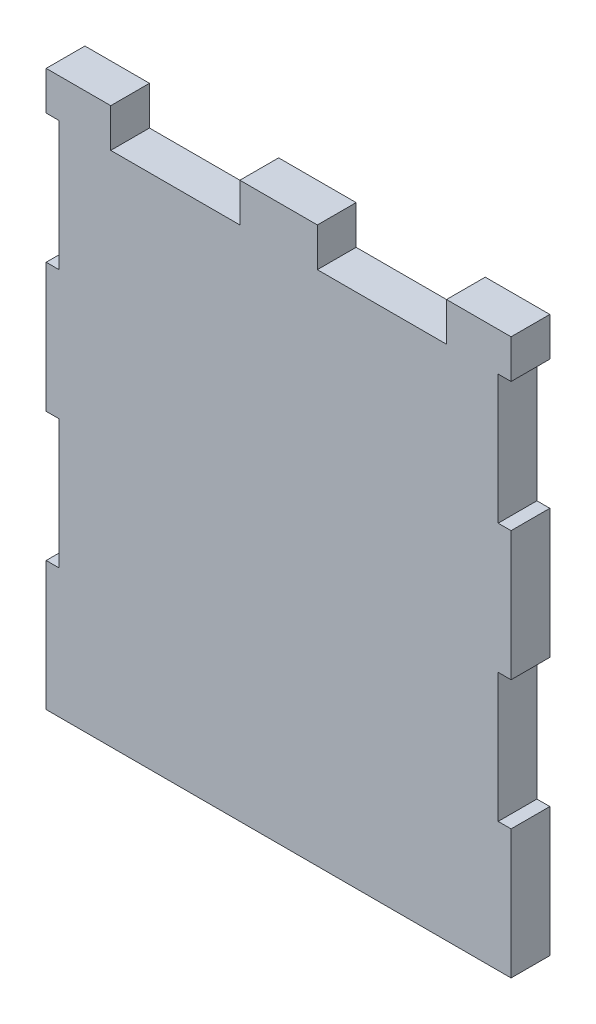
SolidWorks part; units mm, degrees
material "Acrylic (Medium-high impact)"
ref_plane "Front Plane" through (0, 0, 0) normal (0, 0, 1) x (1, 0, 0)
ref_plane "Top Plane" through (0, 0, 0) normal (0, 1, 0) x (1, 0, 0)
ref_plane "Right Plane" through (0, 0, 0) normal (1, 0, 0) x (0, 0, -1)
sketch "Sketch1" plane through (0, 0, 0) normal (0, 0, 1) x (1, 0, 0)
  line L0 (0, 0) -> (0, 40)
  line L1 (0, 40) -> (36, 40)
  line L2 (36, 40) -> (36, 0)
  line L3 (36, 0) -> (0, 0)
  line L4 (18, 0) -> (18, 40) construction
  line L5 (36, 10) -> (35, 10)
  line L6 (0, 0) -> (1, 0)
  line L7 (0, 0) -> (0, 10)
  line L8 (0, 10) -> (1, 10)
  line L9 (1, 0) -> (1, 10)
  line L10 (0, 20) -> (1, 20)
  line L11 (0, 20) -> (0, 30)
  line L12 (0, 30) -> (1, 30)
  line L13 (1, 20) -> (1, 30)
  line L14 (35, 0) -> (35, 10)
  line L15 (36, 0) -> (35, 0)
  line L16 (36, 0) -> (36, 10)
  line L17 (36, 30) -> (35, 30)
  line L18 (35, 20) -> (35, 30)
  line L19 (36, 20) -> (35, 20)
  line L20 (36, 20) -> (36, 30)
  line L21 (1, 20) -> (1, 10)
  line L22 (35, 20) -> (35, 10)
  line L23 (35, 30) -> (35, 40)
  line L24 (1, 30) -> (1, 40)
  line L25 (0, 40) -> (0, 43)
  line L26 (5, 40) -> (15, 40)
  line L27 (5, 40) -> (5, 43)
  line L28 (5, 43) -> (15, 43)
  line L29 (15, 40) -> (15, 43)
  line L30 (21, 40) -> (31, 40)
  line L31 (21, 40) -> (21, 43)
  line L32 (21, 43) -> (31, 43)
  line L33 (31, 40) -> (31, 43)
  line L34 (0, 43) -> (36, 43)
  line L35 (36, 43) -> (36, 40)
  dimension "D1" = 40
  dimension "D2" = 36
  dimension "D3" = 10
  dimension "D4" = 10
  dimension "D5" = 1
  dimension "D6" = 10
  dimension "D7" = 5
  dimension "D8" = 5
  dimension "D9" = 3
extrude "Boss-Extrude1" add sketch "Sketch1" along normal blind 3 contours L3 L4 L1 L24 L13 L21 L9 | L4 L3 L14 L22 L18 L23 L1 | L3 L9 L8 L0 | L10 L13 L12 L0 | L19 L2 L17 L18 | L14 L3 L2 L5 | L34 L25 L1 L27 | L34 L29 L1 L31 | L35 L34 L33 L1
